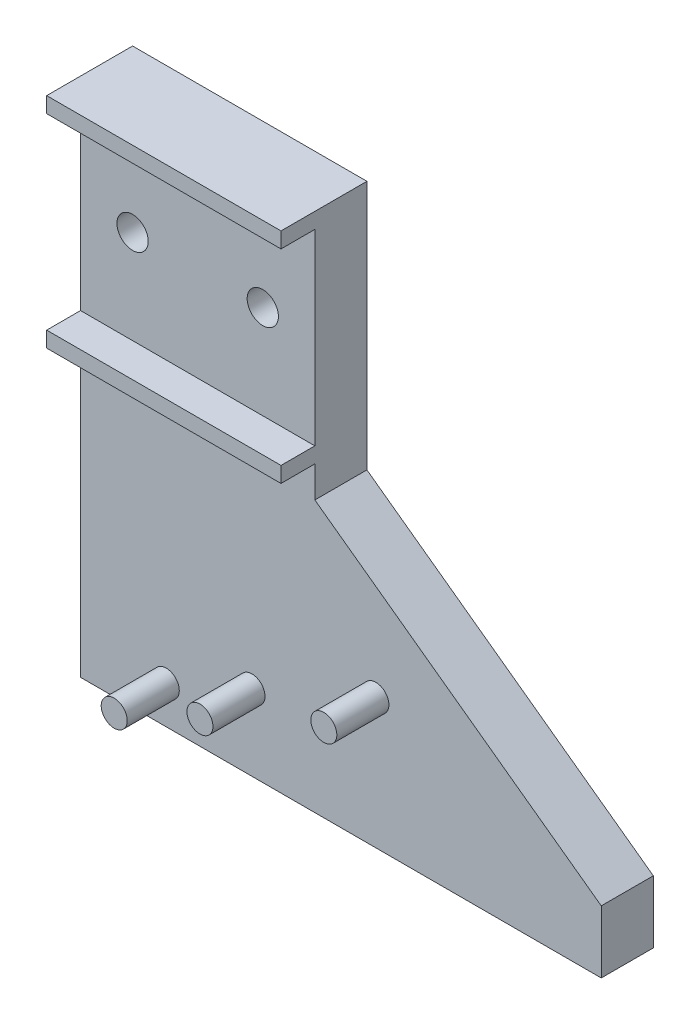
SolidWorks part; units mm, degrees
ref_plane "Front Plane" through (0, 0, 0) normal (0, 0, 1) x (1, 0, 0)
ref_plane "Top Plane" through (0, 0, 0) normal (0, 1, 0) x (1, 0, 0)
ref_plane "Right Plane" through (0, 0, 0) normal (1, 0, 0) x (0, 0, -1)
sketch "Sketch2" plane through (0, 0, 0) normal (0, 0, 1) x (1, 0, 0)
  line L0 (0, 0) -> (100, 0)
  line L1 (100, 0) -> (100, 12)
  line L2 (100, 12) -> (45, 52)
  line L3 (45, 52) -> (45, 100)
  line L4 (45, 100) -> (0, 100)
  line L5 (0, 100) -> (0, 0)
  dimension "D1" = 100
  dimension "D2" = 45
  dimension "D3" = 12
  dimension "D4" = 40
  dimension "D5" = 100
extrude "Boss-Extrude1" add sketch "Sketch2" against normal blind 10
sketch "Sketch3" plane through (0, 0, 0) normal (0, 0, 1) x (1, 0, 0)
  line L0 (45, 52) -> (45, 100) construction
  line L1 (0, 100) -> (45, 100)
  line L2 (0, 100) -> (0, 97)
  line L3 (0, 97) -> (45, 97)
  line L4 (45, 100) -> (45, 97)
  line L5 (0, 100) -> (45, 97) construction
  line L6 (0, 97) -> (45, 100) construction
  line L7 (0, 100) -> (0, 0) construction
  line L8 (0, 61) -> (45, 61)
  line L9 (0, 61) -> (0, 58)
  line L10 (0, 58) -> (45, 58)
  line L11 (45, 61) -> (45, 58)
  line L12 (0, 61) -> (45, 58) construction
  line L13 (0, 58) -> (45, 61) construction
  point P4 (22.5, 98.5)
  point P12 (22.5, 59.5)
  dimension "D1" = 3
  dimension "D2" = 36
extrude "Boss-Extrude2" add sketch "Sketch3" along normal blind 6.5
sketch "Sketch4" plane through (0, 0, 0) normal (0, 0, 1) x (1, 0, 0)
  line L0 (0, 79) -> (45, 79) construction
  line L1 (0, 97) -> (0, 61) construction
  line L2 (45, 61) -> (45, 97) construction
  circle A0 centre (10, 79) radius 3
  circle A1 centre (35, 79) radius 3
  dimension "D1" = 10
  dimension "D3" = 6
  dimension "D2" = 10
extrude "Cut-Extrude2" cut sketch "Sketch4" against normal up to surface (10 mm away) up to face at (48.3333, 44, -10)
sketch "Sketch5" plane through (0, 0, 0) normal (0, 0, 1) x (1, 0, 0)
  line L0 (0, 0) -> (72.5, 32) construction
  line L1 (100, 12) -> (45, 52) construction
  circle A0 centre (16.4673, 7.2683) radius 2.5
  circle A1 centre (32.9346, 14.5366) radius 2.5
  circle A2 centre (56.7207, 25.0353) radius 2.5
  dimension "D1" = 5
  dimension "D2" = 18
  dimension "D3" = 18
  dimension "D4" = 26
extrude "Boss-Extrude3" add sketch "Sketch5" along normal blind 10
